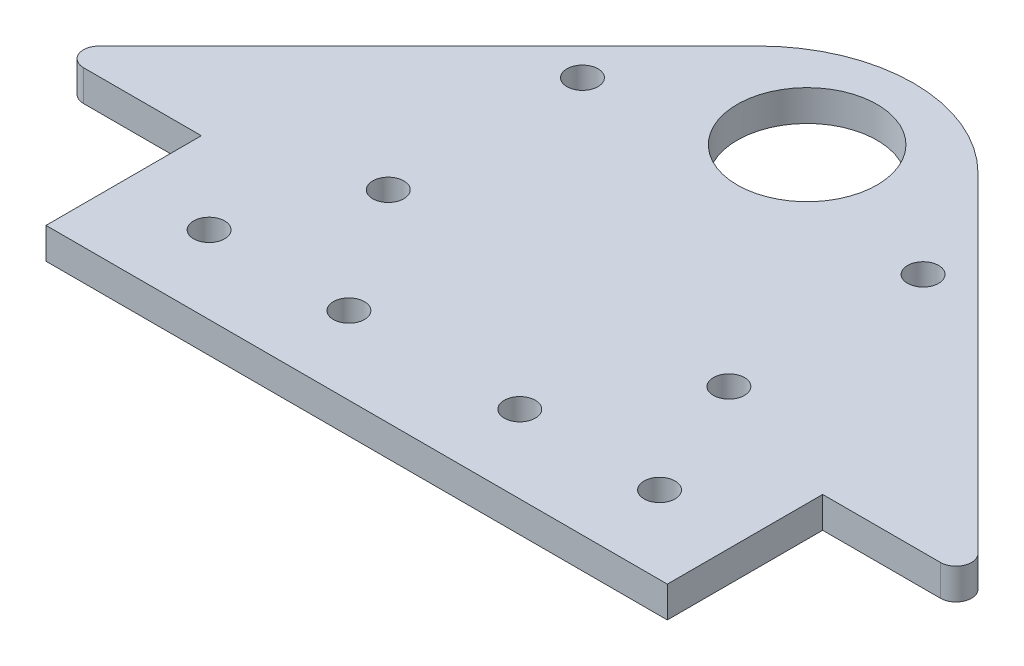
SolidWorks part; units mm, degrees
ref_plane "前视基准面" through (0, 0, 0) normal (0, 0, 1) x (1, 0, 0)
ref_plane "上视基准面" through (0, 0, 0) normal (0, 1, 0) x (1, 0, 0)
ref_plane "右视基准面" through (0, 0, 0) normal (1, 0, 0) x (0, 0, -1)
other "Configuration Table"
sketch "草图1" plane through (0, 0, 0) normal (0, 1, 0) x (1, 0, 0)
  line L0 (0, 0) -> (0, 14.6024) construction
  line L2 (-15, 0) -> (0, 15)
  line L4 (15, 0) -> (0, 15)
  line L5 (-10, 0) -> (-10, -5)
  line L6 (7.75, 7.25) -> (-7.75, 7.25) construction
  line L7 (-5.4822, 0) -> (-5.4822, 9.5178) construction
  line L8 (-10, -5) -> (10, -5)
  line L9 (10, 0) -> (10, -5)
  line L11 (-15, 0) -> (-10, 0)
  line L12 (10, 0) -> (15, 0)
  line L13 (-10, 0) -> (10, 0) construction
  line L14 (-10, -2.5) -> (0, -2.5) construction
  circle A0 centre (0, 9.5) radius 2.25
  circle A2 centre (-5.4822, 7.75) radius 0.5
  circle A3 centre (5.4822, 7.75) radius 0.5
  circle A4 centre (-5.4822, 1.5) radius 0.5
  circle A5 centre (5.4822, 1.5) radius 0.5
  circle A6 centre (-7.25, -2.5) radius 0.5
  circle A7 centre (-2.75, -2.5) radius 0.5
  circle A8 centre (2.75, -2.5) radius 0.5
  circle A9 centre (7.25, -2.5) radius 0.5
  point P24 (0, -5)
  point P33 (0, 0)
  point P34 (0, 0)
  dimension "D3" = 4.5
  dimension "D6" = 1
  dimension "D7" = 1
  dimension "D13" = 1
  dimension "D14" = 1
  dimension "D2" = 15
  dimension "D4" = 5.5
  dimension "D5" = 1.25
  dimension "D8" = 5
  dimension "D9" = 10
  dimension "D10" = 5
  dimension "D11" = 15
  dimension "D12" = 1.5
  dimension "D15" = 2.75
  dimension "D16" = 2.75
extrude "凸台-拉伸1" add sketch "草图1" along normal blind 1
fillet "圆角1" radius 5 1 edges at (0, 0.5, -15)
fillet "圆角3" radius 0.5 2 edges at (-15, 0.5, 0) (15, 0.5, 0)
